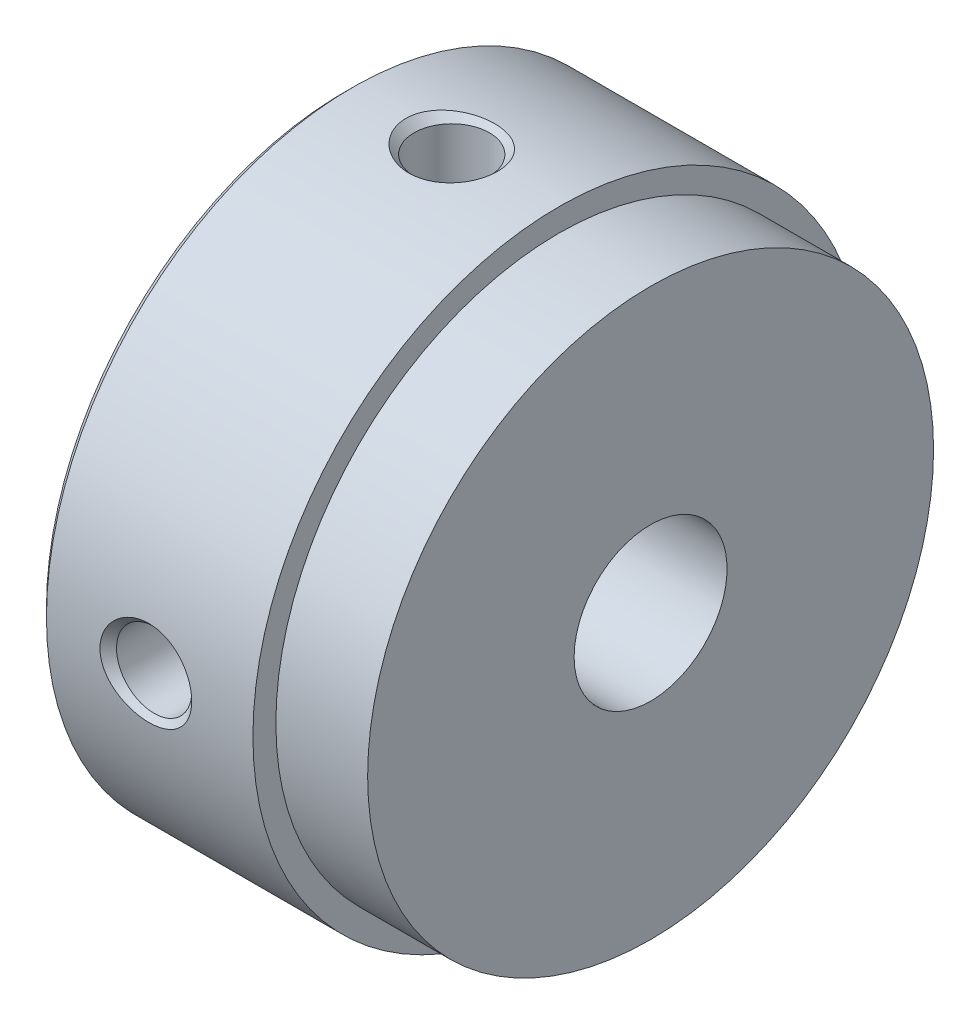
SolidWorks part; units mm, degrees
ref_plane "Front Plane" through (0, 0, 0) normal (0, 0, 1) x (1, 0, 0)
ref_plane "Top Plane" through (0, 0, 0) normal (0, 1, 0) x (1, 0, 0)
ref_plane "Right Plane" through (0, 0, 0) normal (1, 0, 0) x (0, 0, -1)
ref_plane "Plane1" through (0, 0, 0) normal (0, 0, 1) x (1, 0, 0)
sketch "Sketch1" plane through (0, 0, 0) normal (0, 0, 1) x (1, 0, 0)
  line L0 (0, 9.75) -> (0, 2.5)
  line L1 (0, 2.5) -> (10, 2.5)
  line L2 (10, 2.5) -> (10, 9.25)
  line L3 (10, 9.25) -> (7, 9.25)
  line L4 (7, 9.25) -> (7, 10)
  line L5 (7, 10) -> (0.25, 10)
  line L6 (0.25, 10) -> (0, 9.75)
  line L7 (10, 0) -> (0, 0) construction
revolve "Revolve1" add sketch "Sketch1" angle 360 about L7
ref_plane "Plane2" through (3.5, 0, 0) normal (1, 0, 0) x (0, 0, -1)
sketch "Sketch2" plane through (3.5, 0, 0) normal (1, 0, 0) x (0, 0, -1)
  line L0 (0, 10) -> (1.5, 10)
  line L1 (1.5, 10) -> (1.2295, 9.7295)
  line L2 (1.2295, 9.7295) -> (1.2295, 0)
  line L3 (1.2295, 0) -> (0, 0)
  line L4 (0, 0) -> (0, 10)
  line L5 (0, 0) -> (0, 10) construction
revolve "Cut-Revolve1" cut sketch "Sketch2" angle 360 about L5
ref_plane "Plane3" through (3.5, 0, 0) normal (1, 0, 0) x (0, 0, -1)
sketch "Sketch3" plane through (3.5, 0, 0) normal (1, 0, 0) x (0, 0, -1)
  line L0 (-10, 0) -> (-10, 1.5)
  line L1 (-10, 1.5) -> (-9.7295, 1.2295)
  line L2 (-9.7295, 1.2295) -> (0, 1.2295)
  line L3 (0, 1.2295) -> (0, 0)
  line L4 (0, 0) -> (-10, 0)
  line L5 (0, 0) -> (-10, 0) construction
revolve "Cut-Revolve2" cut sketch "Sketch3" angle 360 about L5
